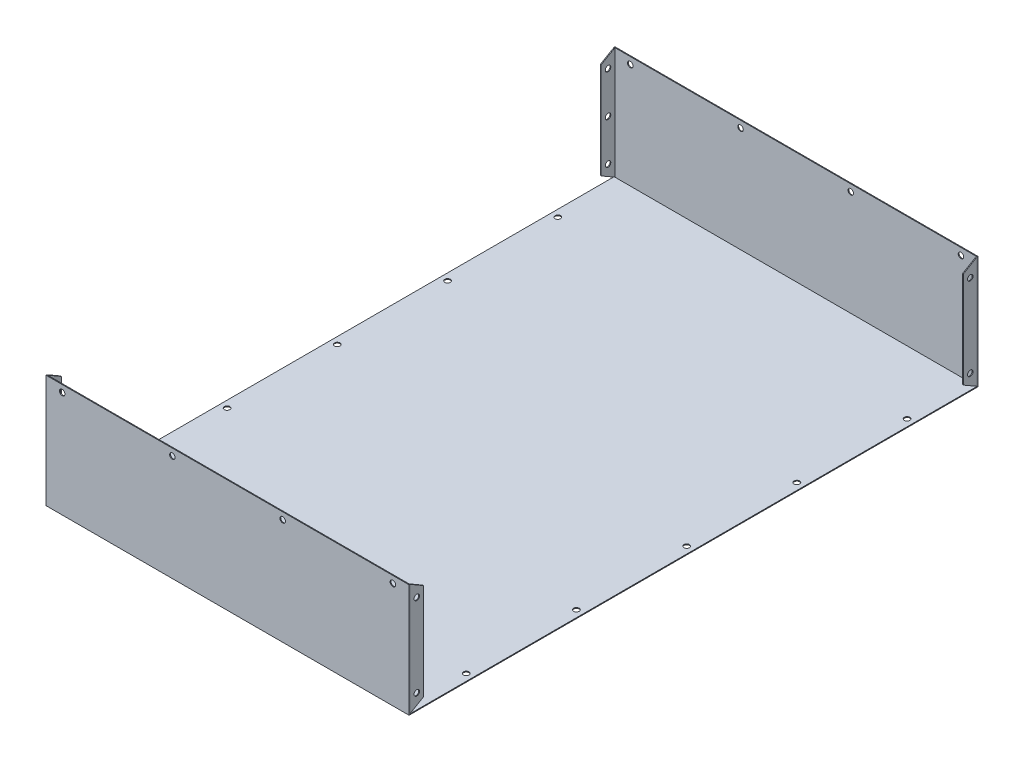
SolidWorks part; units mm, degrees
material "AISI 316 Нержавеющая сталь, лист (SS)"
ref_plane "Спереди" through (0, 0, 0) normal (0, 0, 1) x (1, 0, 0)
ref_plane "Сверху" through (0, 0, 0) normal (0, 1, 0) x (1, 0, 0)
ref_plane "Справа" through (0, 0, 0) normal (1, 0, 0) x (0, 0, -1)
other "Configuration Table"
sketch "Эскиз1" plane through (0, 0, 0) normal (0, 1, 0) x (1, 0, 0)
  line L0 (0, -206.45) -> (0, 206.45) construction
  line L1 (-131.75, 206.45) -> (131.75, 206.45)
  line L2 (-131.75, 206.45) -> (-131.75, -206.45)
  line L3 (-131.75, -206.45) -> (131.75, -206.45)
  line L4 (131.75, 206.45) -> (131.75, -206.45)
  line L5 (-131.75, 0) -> (131.75, 0) construction
  dimension "D1" = 412.9
  dimension "D2" = 263.5
extrude "Бобышка-Вытянуть1" add sketch "Эскиз1" along normal blind 0.6
sketch "Эскиз2" plane through (131.75, 0, 0) normal (1, 0, 0) x (0, 0, -1)
  line L1 (-206.45, 0) -> (-205.85, 0)
  line L2 (-206.45, 0) -> (-206.45, 82)
  line L3 (-206.45, 82) -> (-205.85, 82)
  line L4 (-205.85, 0) -> (-205.85, 82)
  line L5 (206.45, 0) -> (205.85, 0)
  line L6 (206.45, 0) -> (206.45, 82)
  line L7 (206.45, 82) -> (205.85, 82)
  line L8 (205.85, 0) -> (205.85, 82)
  dimension "D1" = 0.6
  dimension "D2" = 82
  dimension "D3" = 0.6
  dimension "D4" = 82
extrude "Бобышка-Вытянуть2" add sketch "Эскиз2" against normal up to surface (263.5 mm away) up to face at (-131.75, 0.3, 0)
sketch "Эскиз3" plane through (-131.75, 0, 0) normal (-1, 0, 0) x (0, 0, 1)
  line L0 (-205.85, 82) -> (-195.85, 76.2265)
  line L1 (-195.85, 76.2265) -> (-195.85, 6.3735)
  line L2 (-195.85, 6.3735) -> (-205.85, 0.6)
  line L3 (-205.85, 0.6) -> (-205.85, 82)
  line L4 (205.85, 0.6) -> (195.85, 6.3735)
  line L5 (195.85, 6.3735) -> (195.85, 76.2265)
  line L6 (195.85, 76.2265) -> (205.85, 82)
  line L7 (205.85, 82) -> (205.85, 0.6)
  line L8 (-200.85, 71.3) -> (-200.85, 11.3) construction
  line L9 (200.85, 71.3) -> (200.85, 11.3) construction
  line L10 (-195.85, 41.3) -> (195.85, 41.3) construction
  line L12 (206.45, 82) -> (206.45, 0) construction
  circle A0 centre (-200.85, 71.3) radius 2
  circle A1 centre (200.85, 71.3) radius 2
  circle A2 centre (200.85, 41.3) radius 2
  circle A3 centre (200.85, 11.3) radius 2
  circle A4 centre (-200.85, 41.3) radius 2
  circle A5 centre (-200.85, 11.3) radius 2
  dimension "D5" = 4
  dimension "D1" = 60
  dimension "D2" = 60
  dimension "D3" = 60
  dimension "D4" = 60
  dimension "D6" = 10
  dimension "D7" = 10
  dimension "D10" = 401.7
  dimension "D11" = 60
  dimension "D8" = 2
  dimension "D9" = 3
extrude "Бобышка-Вытянуть3" add sketch "Эскиз3" against normal blind 0.6
sketch "Эскиз4" plane through (131.75, 0, 0) normal (1, 0, 0) x (0, 0, -1)
  line L0 (205.85, 0.6) -> (195.85, 6.3735) construction
  line L1 (195.85, 76.2265) -> (205.85, 82) construction
  line L2 (205.85, 82) -> (205.85, 0.6) construction
  line L3 (195.85, 6.3735) -> (195.85, 76.2265) construction
  line L4 (-195.85, 6.3735) -> (-205.85, 0.6) construction
  line L5 (-205.85, 0.6) -> (-205.85, 82) construction
  line L6 (-205.85, 82) -> (-195.85, 76.2265) construction
  line L7 (-195.85, 76.2265) -> (-195.85, 6.3735) construction
  line L8 (205.85, 0.6) -> (195.85, 6.3735)
  line L9 (195.85, 76.2265) -> (205.85, 82)
  line L10 (205.85, 82) -> (205.85, 0.6)
  line L11 (195.85, 6.3735) -> (195.85, 76.2265)
  line L12 (-195.85, 6.3735) -> (-205.85, 0.6)
  line L13 (-205.85, 0.6) -> (-205.85, 82)
  line L14 (-205.85, 82) -> (-195.85, 76.2265)
  line L15 (-195.85, 76.2265) -> (-195.85, 6.3735)
  circle A0 centre (200.85, 11.3) radius 2 construction
  circle A1 centre (200.85, 71.3) radius 2 construction
  circle A2 centre (-200.85, 11.3) radius 2 construction
  circle A3 centre (-200.85, 71.3) radius 2 construction
  circle A4 centre (200.85, 11.3) radius 2
  circle A5 centre (200.85, 71.3) radius 2
  circle A6 centre (-200.85, 11.3) radius 2
  circle A7 centre (-200.85, 71.3) radius 2
extrude "Бобышка-Вытянуть4" add sketch "Эскиз4" against normal blind 0.6 separate body
sketch "Эскиз6" plane through (0, 0.6, 0) normal (0, 1, 0) x (1, 0, 0)
  line L0 (-131.75, 205.85) -> (-131.75, -205.85) construction
  line L1 (-131.75, -196.45) -> (-121.75, -196.45)
  line L2 (-131.75, -196.45) -> (-131.75, 196.45)
  line L3 (-131.75, 196.45) -> (-121.75, 196.45)
  line L4 (-121.75, -196.45) -> (-121.75, 196.45)
  line L5 (-131.75, 206.45) -> (131.75, 206.45) construction
  line L6 (-131.75, -206.45) -> (131.75, -206.45) construction
  line L7 (-126.75, -196.45) -> (-126.75, 196.45) construction
  line L8 (-131.75, 0) -> (-121.75, 0) construction
  line L9 (121.75, -196.45) -> (131.75, -196.45)
  line L10 (121.75, -196.45) -> (121.75, 196.45)
  line L11 (121.75, 196.45) -> (131.75, 196.45)
  line L12 (131.75, -196.45) -> (131.75, 196.45)
  line L13 (126.75, -196.45) -> (126.75, 196.45) construction
  line L14 (121.75, 0) -> (131.75, 0) construction
  line L15 (131.75, -205.85) -> (131.75, 205.85) construction
  circle A0 centre (-126.75, -160) radius 2
  circle A1 centre (-126.75, -80) radius 2
  circle A2 centre (-126.75, 0) radius 2
  circle A3 centre (-126.75, 80) radius 2
  circle A4 centre (-126.75, 160) radius 2
  circle A5 centre (126.75, -160) radius 2
  circle A6 centre (126.75, -80) radius 2
  circle A7 centre (126.75, 0) radius 2
  circle A8 centre (126.75, 80) radius 2
  circle A9 centre (126.75, 160) radius 2
  dimension "D4" = 4
  dimension "D7" = 4
  dimension "D1" = 10
  dimension "D2" = 10
  dimension "D3" = 10
  dimension "D6" = 80
  dimension "D8" = 80
  dimension "D9" = 10
  dimension "D10" = 10
  dimension "D11" = 10
  dimension "D12" = 80
  dimension "D13" = 80
  dimension "D14" = 80
  dimension "D5" = 5
extrude "Вырез-Вытянуть1" cut sketch "Эскиз6" against normal through all contours A6 | A5 | A7 | A8 | A9 | A1 | A2 | A0 | A3 | A4
sketch "Эскиз7" plane through (0, 0, -206.45) normal (0, 0, -1) x (-1, 0, 0)
  line L0 (-131.75, 72) -> (131.75, 72)
  line L1 (-131.75, 82) -> (-131.75, 0) construction
  line L2 (131.75, 82) -> (131.75, 0) construction
  line L3 (131.75, 82) -> (-131.75, 82) construction
  line L4 (-131.75, 77) -> (131.75, 77) construction
  line L5 (0, 82) -> (0, 72) construction
  circle A0 centre (-120, 77) radius 2
  circle A1 centre (-40, 77) radius 2
  circle A2 centre (40, 77) radius 2
  circle A3 centre (120, 77) radius 2
  dimension "D2" = 4
  dimension "D1" = 10
  dimension "D4" = 80
  dimension "D3" = 4
extrude "Вырез-Вытянуть2" cut sketch "Эскиз7" against normal up to surface (412.9 mm away) contours A0 | A1 | A2 | A3 up to face at (0, 41, 206.45)
